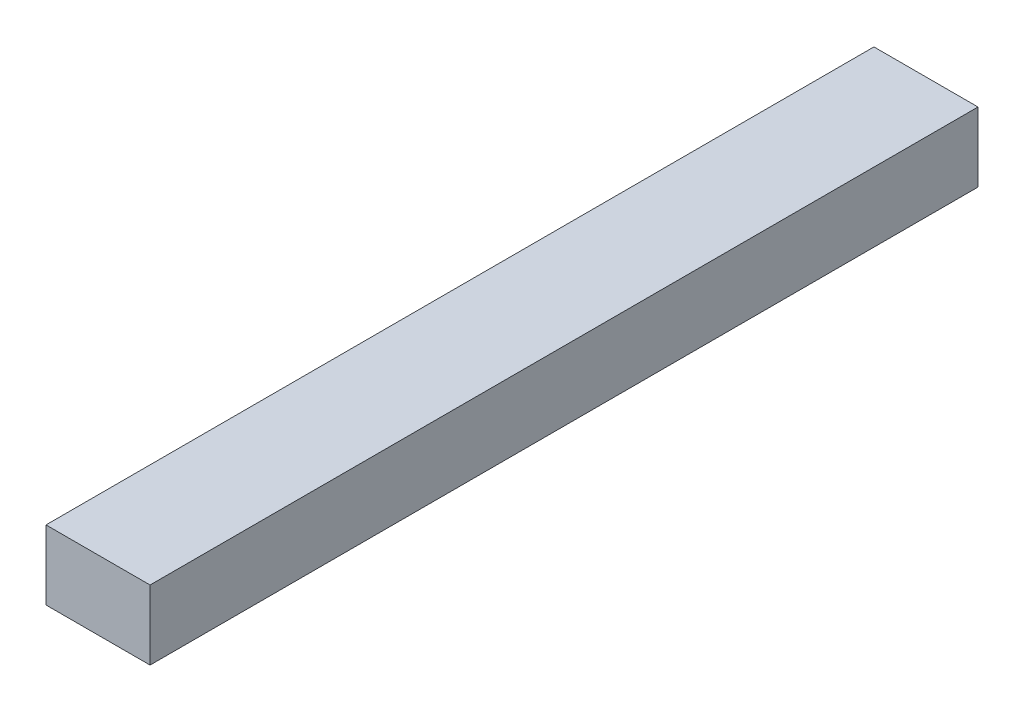
SolidWorks part; units mm, degrees
material "Beech"
ref_plane "Front Plane" through (0, 0, 0) normal (0, 0, 1) x (1, 0, 0)
ref_plane "Top Plane" through (0, 0, 0) normal (0, 1, 0) x (1, 0, 0)
ref_plane "Right Plane" through (0, 0, 0) normal (1, 0, 0) x (0, 0, -1)
sketch "Sketch1" plane through (0, 0, 0) normal (0, 0, 1) x (1, 0, 0)
  line L0 (-47.169, 8.2481) -> (-2.169, 8.2481)
  line L1 (-2.169, 8.2481) -> (-2.169, 38.2481)
  line L2 (-2.169, 38.2481) -> (-47.169, 38.2481)
  line L3 (-47.169, 38.2481) -> (-47.169, 8.2481)
extrude "Boss-Extrude1" add sketch "Sketch1" along normal blind 358
